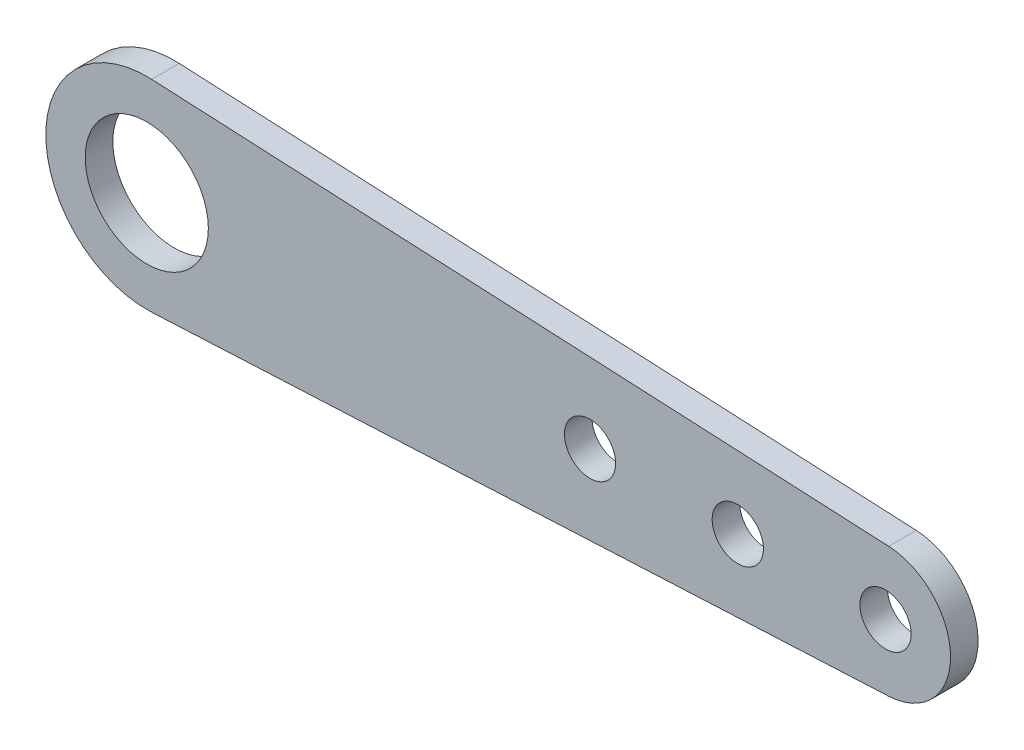
SolidWorks part; units mm, degrees
material "AISI 4130 Steel, annealed at 865C"
ref_plane "Front Plane" through (0, 0, 0) normal (0, 0, 1) x (1, 0, 0)
ref_plane "Top Plane" through (0, 0, 0) normal (0, 1, 0) x (1, 0, 0)
ref_plane "Right Plane" through (0, 0, 0) normal (1, 0, 0) x (0, 0, -1)
sketch "Sketch1" plane through (0, 0, 0) normal (0, 0, 1) x (1, 0, 0)
  line L0 (0, 0) -> (57.15, 0) construction
  line L1 (57.15, 0) -> (76.2, 0) construction
  line L2 (0.6335, 13.0021) -> (95.6579, 8.3721)
  line L3 (0.6335, -13.0021) -> (95.6579, -8.3721)
  arc A0 (0.6335, 13.0021) -> (0.6335, -13.0021) centre (0, 0) ccw
  circle A1 centre (0, 0) radius 7.9375
  circle A2 centre (57.15, 0) radius 3.302
  circle A3 centre (76.2, 0) radius 3.302
  circle A4 centre (95.25, 0) radius 3.302
  arc A5 (95.6579, -8.3721) -> (95.6579, 8.3721) centre (95.25, 0) ccw
  dimension "D1" = 15.875
  dimension "D2" = 5.08
  dimension "D7" = 5.08
  dimension "D3" = 76.2
  dimension "D4" = 19.05
  dimension "D5" = 3
extrude "Extrude - Body" add sketch "Sketch1" along normal blind 3.556
equation "\"Torsion bar hole OD\"= 0.625in"
equation "\"DL Hole ID\"= 0.25"
equation "\"Dist. to middle DL hole\"= 3.0in"
equation "\"Dist. b/w DL holes\"= 0.75in"
equation "\"D1@Sketch1\"=\"Torsion bar hole OD\""
equation "\"D3@Sketch1\"=\"Dist. to middle DL hole\""
equation "\"D4@Sketch1\"=\"Dist. b/w DL holes\""
equation "\"Lever thickness\"= 0.14in"
equation "\"D1@Extrude - Body\"=\"Lever thickness\""
